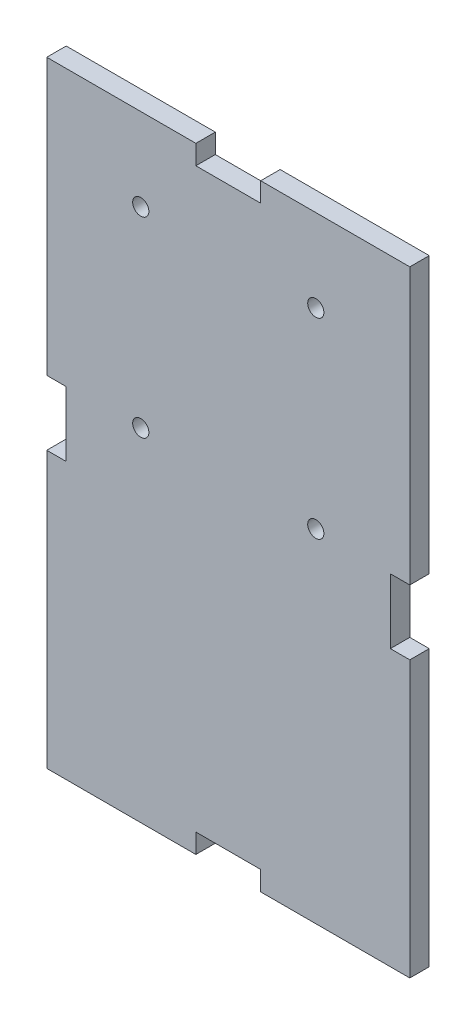
SolidWorks part; units mm, degrees
ref_plane "Front Plane" through (0, 0, 0) normal (0, 0, 1) x (1, 0, 0)
ref_plane "Top Plane" through (0, 0, 0) normal (0, 1, 0) x (1, 0, 0)
ref_plane "Right Plane" through (0, 0, 0) normal (1, 0, 0) x (0, 0, -1)
sketch "Sketch1" plane through (0, 0, 0) normal (0, 0, 1) x (1, 0, 0)
  line L0 (0.1293, 43.9602) -> (0.1293, -45.0398) construction
  line L1 (28.1293, -5.5398) -> (28.1293, -48.0398)
  line L2 (25.1293, -48.0398) -> (28.1293, -48.0398)
  line L3 (25.1293, -48.0398) -> (5.1293, -48.0398)
  line L4 (25.1293, 46.9602) -> (28.1293, 46.9602)
  line L5 (28.1293, 46.9602) -> (28.1293, 4.4602)
  line L6 (25.1293, 4.4602) -> (28.1293, 4.4602)
  line L7 (25.1293, 4.4602) -> (25.1293, -5.5398)
  line L8 (25.1293, -5.5398) -> (28.1293, -5.5398)
  line L9 (5.1293, -45.0398) -> (5.1293, -48.0398)
  line L10 (25.1293, 46.9602) -> (5.1293, 46.9602)
  line L11 (5.1293, 46.9602) -> (5.1293, 43.9602)
  line L40 (-4.8707, 43.9602) -> (5.1293, 43.9602)
  line L41 (-4.8707, 46.9602) -> (-4.8707, 43.9602)
  line L42 (-24.8707, 46.9602) -> (-4.8707, 46.9602)
  line L43 (-4.8707, -45.0398) -> (-4.8707, -48.0398)
  line L44 (-4.8707, -45.0398) -> (5.1293, -45.0398)
  line L46 (-24.8707, -5.5398) -> (-27.8707, -5.5398)
  line L47 (-24.8707, 4.4602) -> (-24.8707, -5.5398)
  line L48 (-24.8707, 4.4602) -> (-27.8707, 4.4602)
  line L49 (-27.8707, 46.9602) -> (-27.8707, 4.4602)
  line L50 (-24.8707, 46.9602) -> (-27.8707, 46.9602)
  line L59 (-24.8707, -48.0398) -> (-4.8707, -48.0398)
  line L60 (-24.8707, -48.0398) -> (-27.8707, -48.0398)
  line L61 (-27.8707, -5.5398) -> (-27.8707, -48.0398)
  dimension "D1" = 20
  dimension "D2" = 20
  dimension "D3" = 95
  dimension "D4" = 3
  dimension "D6" = 10
extrude "Boss-Extrude1" add sketch "Sketch1" along normal blind 3
sketch "Sketch2" plane through (0, 0, 3) normal (0, 0, 1) x (1, 0, 0)
  circle A0 centre (13.6293, 34.2258) radius 1.25
  circle A1 centre (13.6293, 4.6945) radius 1.25
  circle A2 centre (-13.3707, 34.2258) radius 1.25
  circle A3 centre (-13.3707, 4.6945) radius 1.25
  dimension "D1" = 2.5
  dimension "D2" = 29.5312
  dimension "D3" = 27
extrude "Cut-Extrude1" cut sketch "Sketch2" against normal up to surface (3 mm away) up to face at (0.1293, -0.5398, 0)
